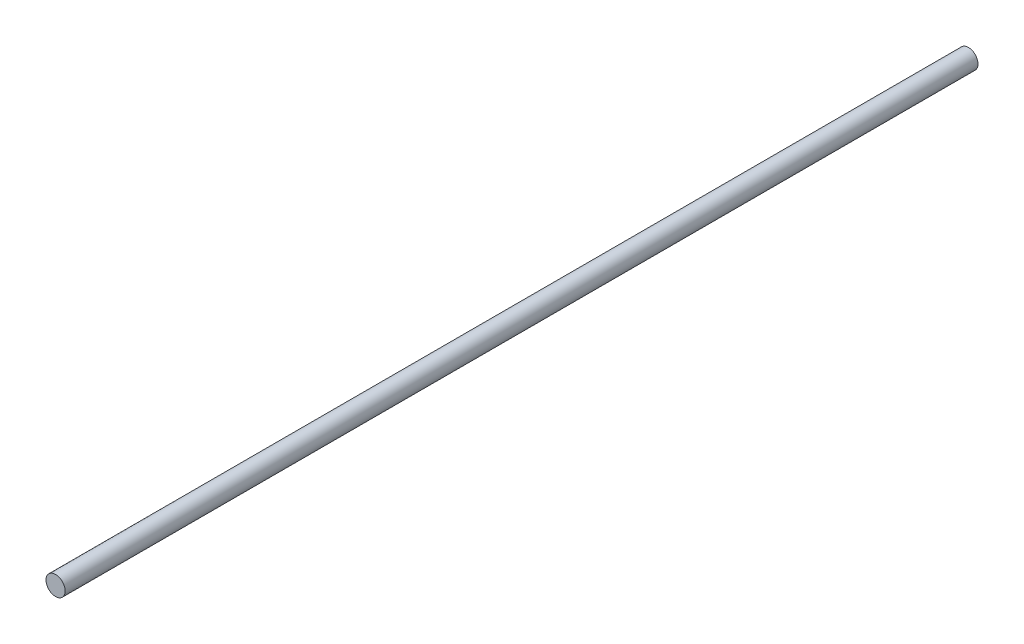
SolidWorks part; units mm, degrees
ref_plane "Front Plane" through (0, 0, 0) normal (0, 0, 1) x (1, 0, 0)
ref_plane "Top Plane" through (0, 0, 0) normal (0, 1, 0) x (1, 0, 0)
ref_plane "Right Plane" through (0, 0, 0) normal (1, 0, 0) x (0, 0, -1)
sketch "Sketch1" plane through (0, 0, 0) normal (0, 0, 1) x (1, 0, 0)
  circle A0 centre (0, 0) radius 4
  dimension "D1" = 8
extrude "Boss-Extrude1" add sketch "Sketch1" along normal blind 381
